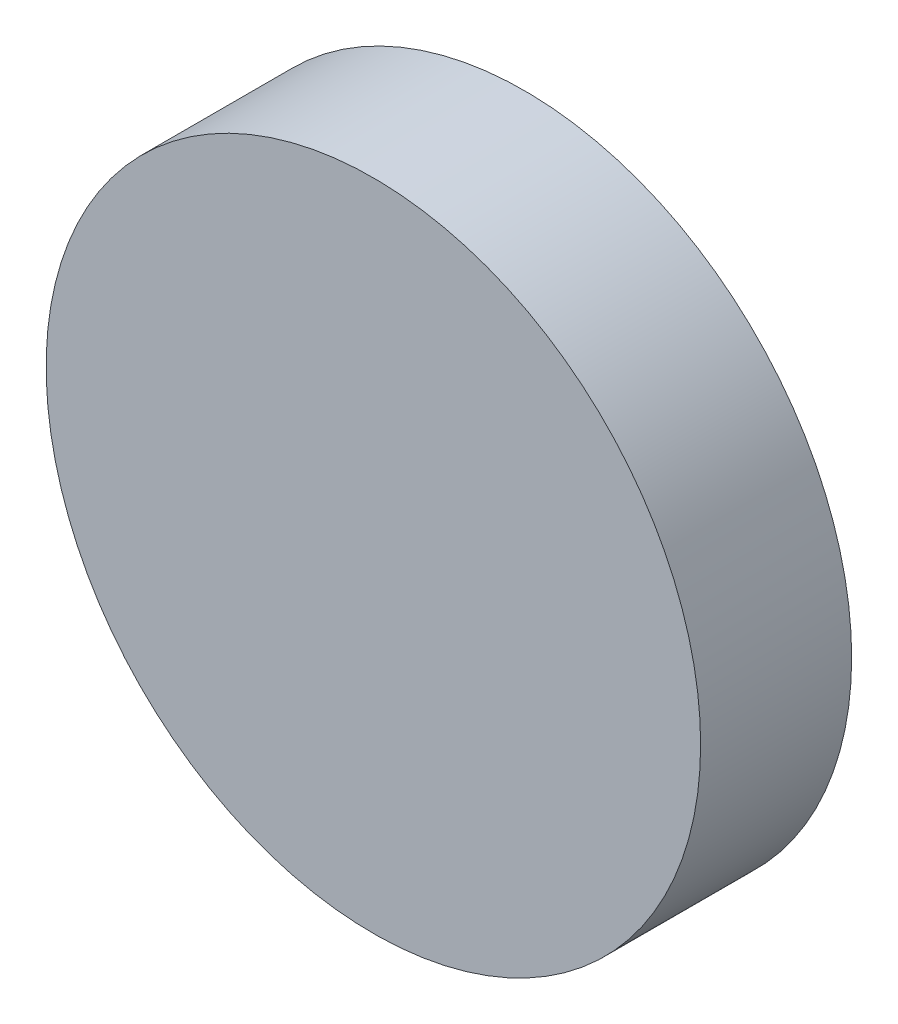
SolidWorks part; units mm, degrees
ref_plane "前视基准面" through (0, 0, 0) normal (0, 0, 1) x (1, 0, 0)
ref_plane "上视基准面" through (0, 0, 0) normal (0, 1, 0) x (1, 0, 0)
ref_plane "右视基准面" through (0, 0, 0) normal (1, 0, 0) x (0, 0, -1)
sketch "草图1" plane through (0, 0, 0) normal (0, 0, 1) x (1, 0, 0)
  circle A0 centre (0, 0) radius 32.5
  dimension "D1" = 65
extrude "凸台-拉伸1" add sketch "草图1" along normal blind 15
